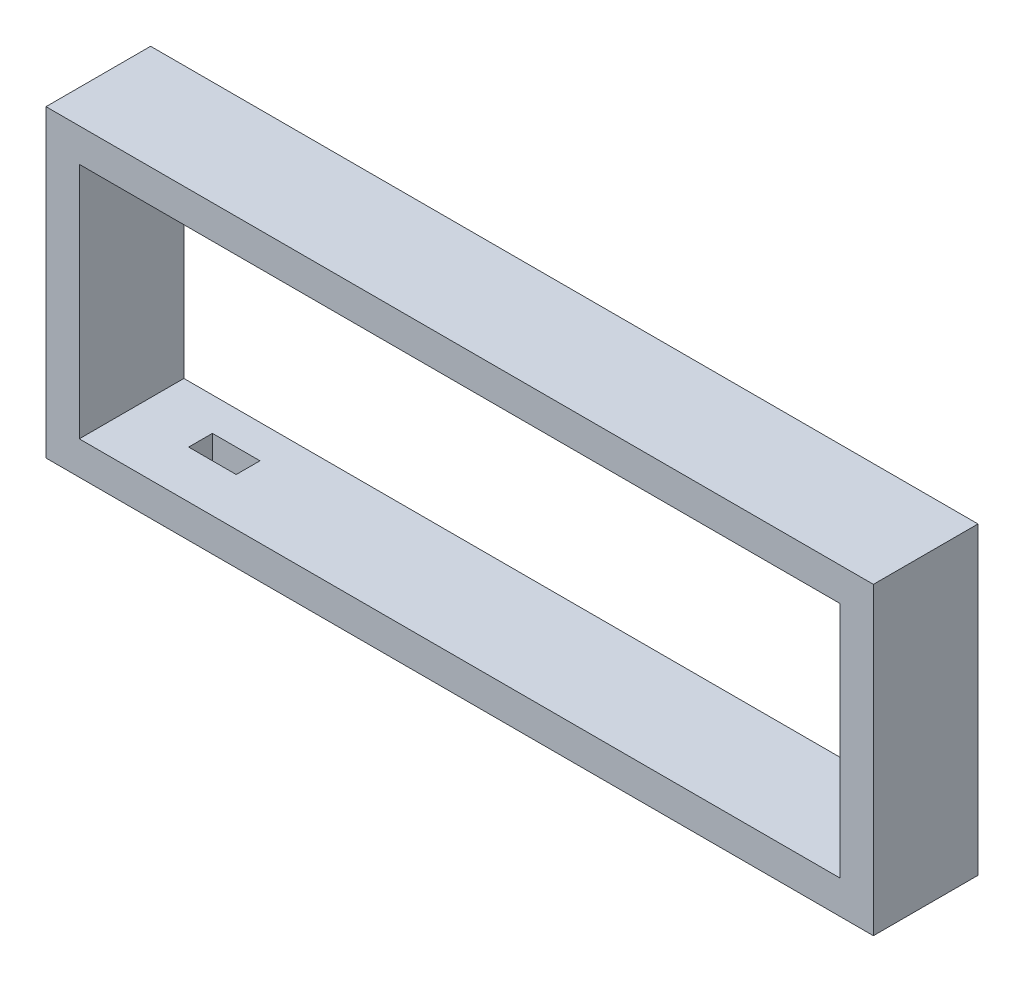
SolidWorks part; units mm, degrees
ref_plane "Přední rovina" through (0, 0, 0) normal (0, 0, 1) x (1, 0, 0)
ref_plane "Horní rovina" through (0, 0, 0) normal (0, 1, 0) x (1, 0, 0)
ref_plane "Pravá rovina" through (0, 0, 0) normal (1, 0, 0) x (0, 0, -1)
sketch "Skica1" plane through (0, 0, 0) normal (0, 0, 1) x (1, 0, 0)
  line L0 (-7, -7) -> (-7, 57)
  line L1 (0, 0) -> (160, 0)
  line L2 (0, 0) -> (0, 50)
  line L3 (0, 50) -> (160, 50)
  line L4 (160, 0) -> (160, 50)
  line L5 (-7, 57) -> (167, 57)
  line L6 (167, -7) -> (167, 57)
  line L7 (-7, -7) -> (167, -7)
  dimension "D1" = 50
  dimension "D2" = 160
  dimension "D3" = 7
extrude "Přidat vysunutím1" add sketch "Skica1" along normal blind 2
sketch "Skica2" plane through (0, 0, 2) normal (0, 0, 1) x (1, 0, 0)
  line L1 (-7, -7) -> (167, -7)
  line L2 (-7, -7) -> (-7, 57)
  line L3 (-7, 57) -> (167, 57)
  line L4 (167, -7) -> (167, 57)
  line L5 (0, 0) -> (160, 0)
  line L6 (0, 0) -> (0, 50)
  line L7 (0, 50) -> (160, 50)
  line L8 (160, 0) -> (160, 50)
extrude "Přidat vysunutím2" add sketch "Skica2" along normal blind 20
sketch "Skica3" plane through (0, 0, 0) normal (0, 1, 0) x (1, 0, 0)
  line L0 (0, -22) -> (0, 0) construction
  line L1 (13, -12) -> (23, -12)
  line L2 (13, -12) -> (13, -7)
  line L3 (13, -7) -> (23, -7)
  line L4 (23, -12) -> (23, -7)
  line L5 (0, -22) -> (160, -22) construction
  dimension "D1" = 10
  dimension "D2" = 5
  dimension "D3" = 13
  dimension "D4" = 10
extrude "Odebrat vysunutím1" cut sketch "Skica3" against normal through all
